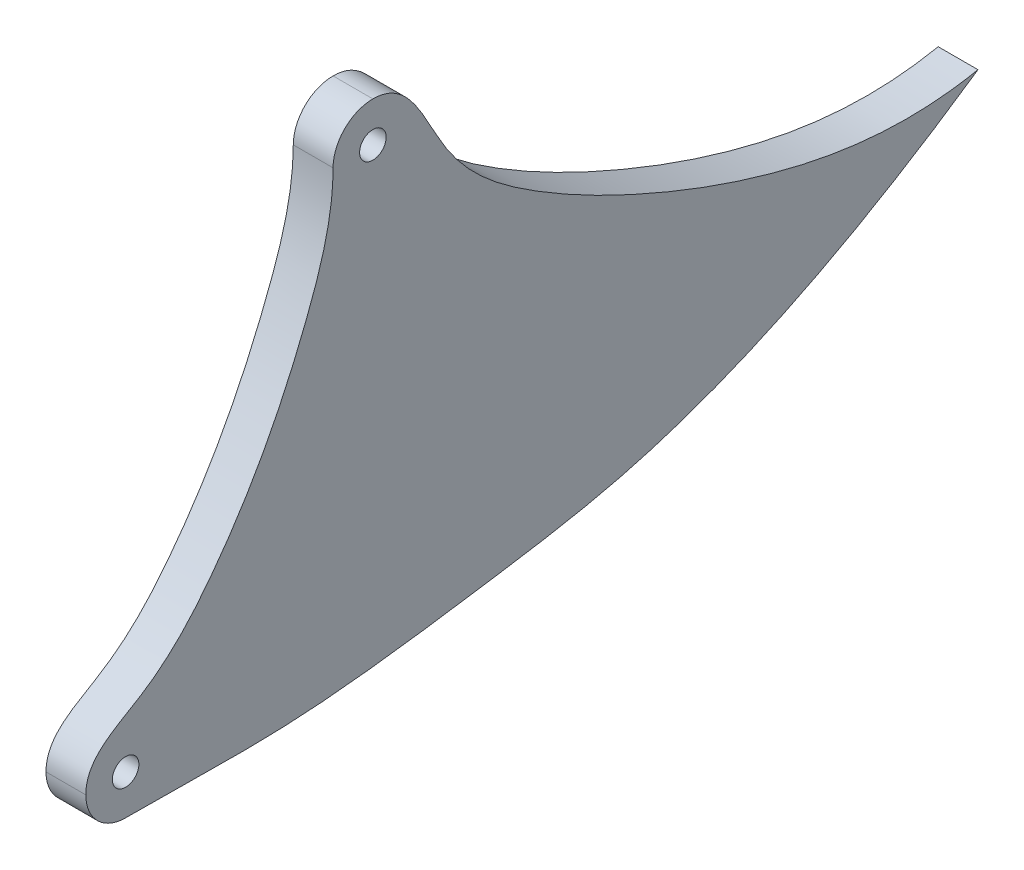
SolidWorks part; units mm, degrees
ref_plane "Front Plane" through (0, 0, 0) normal (1, 0, 0) x (0, 1, 0)
ref_plane "Top Plane" through (0, 0, 0) normal (0, 0, 1) x (0, 1, 0)
ref_plane "Right Plane" through (0, 0, 0) normal (0, 1, 0) x (-1, 0, 0)
sketch "Sketch1" plane through (0, 0, 0) normal (1, 0, 0) x (0, 1, 0)
  line L0 (34.9544, 81.6423) -> (174.7722, 81.6423) construction
  line L1 (65.8943, 10.0491) -> (83.7948, 55.6624)
  line L2 (83.7948, 55.6624) -> (52.1805, 74.3019)
  line L3 (52.1805, 74.3019) -> (65.8943, 10.0491)
  line L4 (83.7948, 55.6624) -> (128.0091, 98.9834)
  line L5 (128.0091, 98.9834) -> (90.89, 132.4822)
  line L6 (90.89, 132.4822) -> (75.2816, 94.0293)
  line L7 (75.2816, 94.0293) -> (83.7948, 55.6624)
  line L8 (52.1805, 74.3019) -> (39.1862, 111.4975)
  line L9 (39.1862, 111.4975) -> (90.89, 132.4822)
  line L10 (39.1862, 111.4975) -> (75.2816, 94.0293)
  line L11 (128.0091, 98.9834) -> (113.2816, 101.8293)
  dimension "D1" = 49
  dimension "D2" = 65.7
  dimension "D3" = 36.7
  dimension "D4" = 61.9
  dimension "D5" = 50
  dimension "D6" = 41.5
  dimension "D7" = 39.3
  dimension "D8" = 55.8
  dimension "D9" = 39.4
  dimension "D10" = 40.1
  dimension "D11" = 15
  dimension "D12" = 7.8
  dimension "D13" = 38
sketch "Sketch3" plane through (0, 0, 0) normal (1, 0, 0) x (0, 1, 0)
  arc A0 (58.6162, 81.9559) -> (42.1912, 73.8395) centre (52.1805, 74.3019) ccw
  arc A2 (88.1385, 46.6551) -> (87.3765, 64.999) centre (83.7948, 55.6624) ccw
  circle A3 centre (128.0091, 98.9834) radius 10
  circle A14 centre (39.1862, 111.4975) radius 1
  circle A15 centre (90.89, 132.4822) radius 1
  circle A22 centre (75.2816, 94.0293) radius 1
  arc A23 (88.1385, 46.6551) -> (65.8943, 10.0491) centre (105.2341, 11.2052) ccw
  arc A28 (42.1912, 73.8395) -> (65.8943, 10.0491) centre (153.7818, 79.0051) ccw
  arc A29 (58.6162, 81.9559) -> (87.3765, 64.999) centre (123.4727, 159.0897) ccw
  circle A31 centre (83.7948, 55.6624) radius 1
  circle A32 centre (52.1805, 74.3019) radius 1
  point P12 (88.1385, 46.6551)
  dimension "D1" = 20
  dimension "D2" = 2
  dimension "D3" = 2
  dimension "D4" = 37.9329
  dimension "D5" = 2
  dimension "D6" = 2
extrude "Boss-Extrude5" add sketch "Sketch3" along normal blind 3 contours A29 A0 A28 A23 A2 A32 A31
scale "Scale1" scale about centroid uniform scaling yes scale factor 2
sketch "Sketch4" plane through (4.5, 0, 0) normal (1, 0, 0) x (0, 1, 0)
  arc A0 (40.08, 101.0113) -> (34.08, 95.0113) centre (40.08, 95.0113) ccw
  arc A1 (109.3084, 57.7323) -> (103.3084, 63.7323) centre (103.3084, 57.7323) ccw
  arc A4 (139.3084, 57.7323) -> (103.3084, 93.7323) centre (103.3084, 57.7323) ccw
  arc A5 (40.08, 131.0113) -> (4.08, 95.0113) centre (40.08, 95.0113) ccw
  spline S0 degree 3 poles (34.08, 95.0113) (34.08, 85.7264) (33.3114, 69.4295) (37.0386, 43.4561) (42.7668, 7.0769) (56.4465, -17.3735) (67.5075, -33.4943) knots 0 0 0 0 0.180012 0.401526 0.562608 1 1 1 1
  spline S1 degree 3 poles (67.5075, -33.4943) (65.2093, -22.1245) (67.8453, -5.2914) (76.1467, 16.9968) (84.6132, 33.7201) (95.4437, 47.5938) (109.3084, 52.2111) (109.3084, 57.7323) knots 0 0 0 0 0.322648 0.479625 0.681873 0.850486 1 1 1 1
  spline S2 degree 3 poles (103.3084, 63.7323) (96.908, 63.7323) (86.5126, 67.0514) (71.5834, 73.7503) (58.7574, 81.9715) (48.7372, 91.0729) (44.7181, 101.0113) (40.08, 101.0113) knots 0 0 0 0 0.240383 0.442269 0.650279 0.840103 1 1 1 1
  spline S3 degree 1 poles (126.0912, -171.9021) (139.3084, 57.7323) knots 0 0 1 1 construction
  spline S4 degree 1 poles (103.3084, 93.7323) (40.08, 131.0113) knots 0 0 1 1 construction
  spline S5 degree 1 poles (4.08, 95.0113) (126.0912, -171.9021) knots 0 0 1 1 construction
  spline S6 degree 3 poles (126.0912, -171.9021) (123.985, -161.4826) (120.8258, -145.8533) (116.6135, -125.0143) (113.4543, -109.385) (110.8217, -96.3606) (108.7155, -85.941) (107.1359, -78.1264) (105.5563, -70.3118) (103.9767, -62.4971) (102.6604, -55.9849) (101.6073, -50.7751) (100.8175, -46.8678) (100.0277, -42.9605) (99.2379, -39.0532) (98.5797, -35.797) (98.0532, -33.1922) (97.7241, -31.564) (97.4609, -30.262) (97.2632, -29.2838) (97.0995, -28.4739) (96.9912, -27.938) (96.9432, -27.7006) (96.9062, -27.5176) (96.8967, -27.4699) (96.8749, -27.3586) (96.8502, -27.2286) (96.8069, -26.9914) (96.7505, -26.6543) (96.6896, -26.2424) (96.6181, -25.686) (96.5465, -24.9738) (96.4897, -24.0884) (96.4627, -23.1686) (96.468, -21.8928) (96.555, -20.1996) (96.8773, -17.2712) (97.4908, -14.0121) (98.3943, -10.4682) (99.489, -6.7271) (100.7877, -2.9391) (102.2824, 0.9013) (103.9218, 4.8201) (105.6821, 8.6423) (107.5082, 12.2053) (108.9136, 14.749) (110.0914, 16.72) (111.0658, 18.251) (111.9266, 19.5418) (112.5687, 20.4042) (113.004, 20.9213) (113.2314, 21.1648) (113.3739, 21.3007) (113.4412, 21.3575) (113.484, 21.3906) (113.5119, 21.4113) (113.5597, 21.4429) (113.5661, 21.4484) (113.821, 21.6004) (114.5701, 22.0211) (116.1709, 22.8843) (119.077, 24.5055) (122.9638, 26.9756) (127.8367, 30.8525) (132.4602, 36.0754) (135.7819, 41.8129) (137.7828, 46.8072) (138.8317, 51.3385) (139.2425, 55.0158) (139.3084, 56.8236) (139.3084, 57.7323) knots -1.365453 -1.365453 -1.365453 -1.365453 -1.069771 -0.921931 -0.77409 -0.626249 -0.552329 -0.478408 -0.404488 -0.330567 -0.256647 -0.219687 -0.182726 -0.145766 -0.108806 -0.071846 -0.053366 -0.034886 -0.025646 -0.016406 -0.007166 -0.002545 -0.00139 -0.000235 0.002075 0.004385 0.006695 0.011315 0.020555 0.029795 0.039035 0.057515 0.075995 0.094475 0.112955 0.149915 0.186876 0.260796 0.297756 0.334716 0.408637 0.445597 0.482557 0.556478 0.593438 0.630398 0.667358 0.685838 0.704318 0.741279 0.759759 0.778239 0.796719 0.815199 0.824439 0.833679 0.842919 0.852159 0.861399 0.870639 0.889119 0.907599 0.92608 0.94456 0.96304 0.97228 0.98152 0.99076 0.99538 1 1 1 1
  spline S7 degree 3 poles (103.3084, 93.7323) (103.202, 93.7323) (103.0077, 93.7391) (102.4728, 93.7929) (101.4344, 93.986) (99.6422, 94.5216) (97.7398, 95.2062) (96.0191, 95.8695) (94.3106, 96.5597) (92.0868, 97.5032) (89.395, 98.734) (86.3386, 100.2847) (83.4196, 101.9345) (80.6153, 103.6957) (78.6448, 105.0717) (77.4057, 105.9962) (76.5865, 106.6242) (75.766, 107.2847) (75.0833, 107.8839) (74.6579, 108.3005) (74.4639, 108.517) (74.3664, 108.6361) (74.3116, 108.7085) (74.2753, 108.7599) (74.243, 108.8093) (74.2228, 108.8396) (73.9253, 109.3301) (73.2129, 110.5475) (72.1093, 112.3734) (70.5137, 114.7914) (68.2365, 117.782) (64.9963, 121.2579) (60.4703, 124.9511) (54.4853, 128.2985) (48.5645, 130.1695) (43.6679, 130.897) (41.2827, 131.0113) (40.08, 131.0113) knots 0 0 0 0 0.03125 0.0625 0.125 0.1875 0.21875 0.25 0.28125 0.3125 0.375 0.4375 0.5 0.5625 0.625 0.640625 0.65625 0.6875 0.71875 0.75 0.78125 0.796875 0.8125 0.828125 0.835938 0.84375 0.859375 0.875 0.890625 0.90625 0.921875 0.9375 0.953125 0.96875 0.984375 0.992188 1 1 1 1
  spline S8 degree 3 poles (4.08, 95.0113) (4.08, 94.2421) (4.0747, 92.6932) (4.0483, 89.6807) (3.9745, 84.4749) (3.8918, 78.4209) (3.9905, 71.89) (4.2221, 66.6863) (4.6005, 61.6004) (5.252, 54.9178) (6.0729, 48.4121) (6.9683, 42.1074) (7.6549, 37.5082) (8.339, 32.9985) (9.0974, 28.2372) (9.964, 23.2977) (10.9868, 18.1698) (12.2215, 12.8412) (14.199, 5.6139) (17.1135, -3.0455) (21.2208, -13.0126) (25.8066, -22.5228) (29.9372, -30.0906) (33.3764, -35.9361) (36.0109, -40.2171) (38.2437, -43.7011) (40.0441, -46.4354) (41.1792, -48.1296) (42.0799, -49.4582) (42.7839, -50.4874) (43.3844, -51.3617) (44.2205, -52.5806) (45.2535, -54.0859) (47.7426, -57.7138) (51.4721, -63.1493) (56.4472, -70.4002) (61.4216, -77.6501) (68.0545, -87.3171) (76.3454, -99.4006) (86.2945, -113.9009) (96.2437, -128.4012) (109.5092, -147.735) (119.4584, -162.2353) (126.0912, -171.9021) knots 0 0 0 0 0.016393 0.032785 0.065571 0.131141 0.163927 0.196712 0.229498 0.262283 0.327854 0.360639 0.393424 0.42621 0.458995 0.49178 0.524566 0.557351 0.590137 0.655707 0.721278 0.786849 0.852419 0.885205 0.91799 0.950776 0.967168 0.983561 0.991757 0.999954 1.00815 1.016346 1.032739 1.049132 1.114702 1.180273 1.245844 1.311415 1.442556 1.573697 1.704839 1.83598 2.098263 2.098263 2.098263 2.098263
  point P1 (63.8021, -28.6363)
  point P4 (243.2825, 104.4176)
  point P6 (67.2612, -32.954)
  point P20 (47.8768, 95.0113)
  point P24 (55.9858, 85.3548)
  point P27 (70.5343, 75.457)
  point P29 (85.6791, 67.7057)
  point P31 (68.5071, 75.934)
  point P32 (58.8478, 82.7313)
  point P33 (71.8802, 74.026)
  point P34 (48.8666, 92.8079)
  point P35 (58.7405, 82.5047)
  point P36 (97.8761, 47.0174)
  point P37 (85.6791, 34.2319)
  point P38 (75.8607, 15.4482)
  point P39 (70.2054, 0)
  point P40 (54.5006, -15.0727)
  point P41 (58.7405, -19.8673)
  point P42 (0, 0)
  point P43 (67.5075, -33.4943)
  point P44 (44.7564, 17.4679)
  point P45 (37.4852, 40.8971)
  point P46 (41.5248, 19.4877)
  point P48 (67.5075, -33.4943)
  arc M8 (110.472, 76.4054) -> (52.9513, 110.3191) centre (182.6643, 264.5869) cw
  arc M9 (52.9513, 110.3191) -> (20.1014, 94.0865) centre (40.08, 95.0113) ccw
  arc M10 (20.1014, 94.0865) -> (67.5075, -33.4943) centre (243.2825, 104.4176) ccw
  arc M11 (67.5075, -33.4943) -> (111.996, 39.7177) centre (146.1872, -31.1822) cw
  arc M12 (111.996, 39.7177) -> (110.472, 76.4054) centre (103.3084, 57.7323) ccw
  dimension "D1" = 12
  dimension "D2" = 12
  dimension "D3" = 30
extrude "Cut-Extrude5" cut sketch "Sketch4" against normal through all both and the other way through all contours A5 S8 S6 A4 S7 M8 M12 M11 M10 M9 | S2 A1 S1 S0 A0 M11 M12 M8 M9 M10
